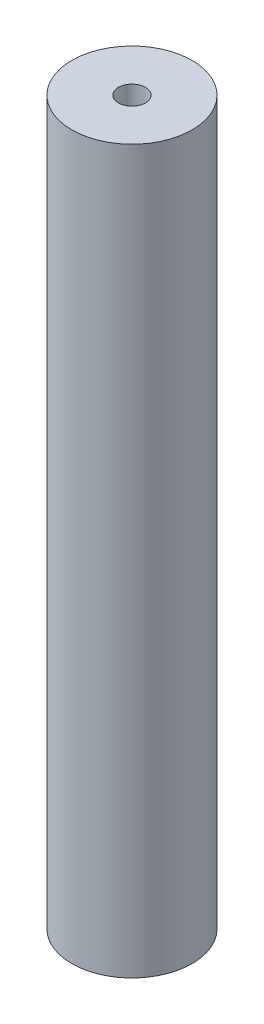
SolidWorks part; units mm, degrees
material "Polylactic Acid (PLA)"
ref_plane "Front Plane" through (0, 0, 0) normal (0, 0, 1) x (1, 0, 0)
ref_plane "Top Plane" through (0, 0, 0) normal (0, 1, 0) x (1, 0, 0)
ref_plane "Right Plane" through (0, 0, 0) normal (1, 0, 0) x (0, 0, -1)
sketch "Sketch1" plane through (0, 0, 0) normal (0, 1, 0) x (1, 0, 0)
  circle A0 centre (0, 0) radius 10
  dimension "D1" = 20
extrude "Boss-Extrude1" add sketch "Sketch1" along normal blind 120
sketch "Sketch2" plane through (0, 120, 0) normal (0, 1, 0) x (1, 0, 0)
  circle A0 centre (0, 0) radius 2.25
extrude "Cut-Extrude1" cut sketch "Sketch2" against normal blind 120
